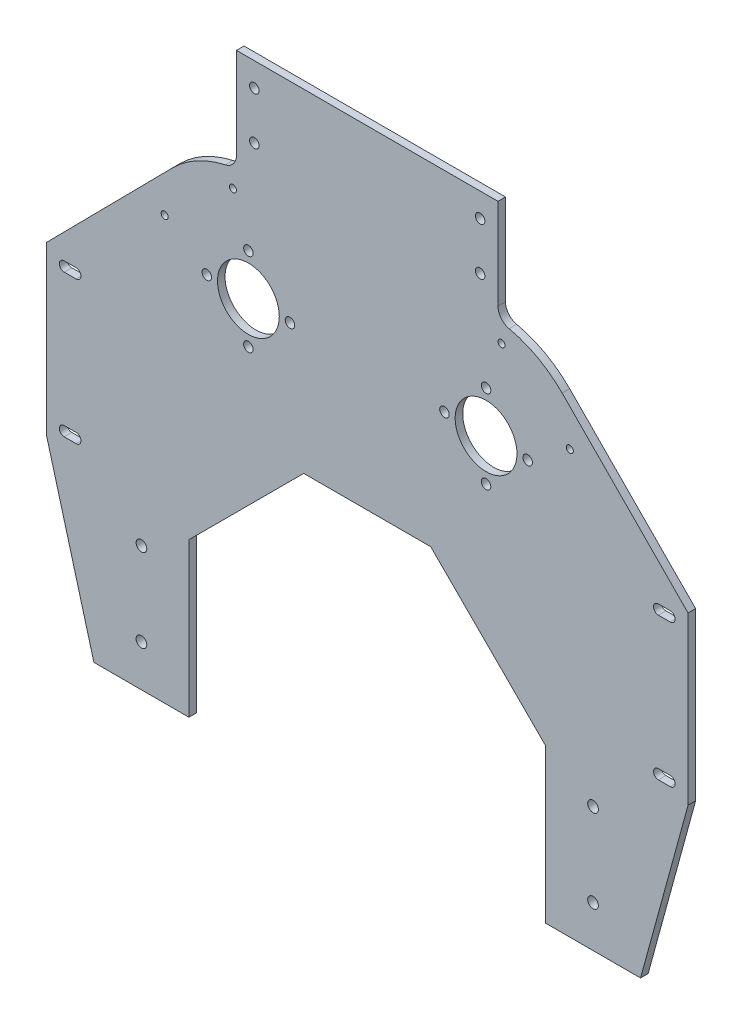
SolidWorks part; units mm, degrees
ref_plane "Front Plane" through (0, 0, 0) normal (0, 0, 1) x (1, 0, 0)
ref_plane "Top Plane" through (0, 0, 0) normal (0, 1, 0) x (1, 0, 0)
ref_plane "Right Plane" through (0, 0, 0) normal (1, 0, 0) x (0, 0, -1)
sketch "Sketch1" plane through (0, 0, 0) normal (0, 0, 1) x (1, 0, 0)
  line L1 (-100, -75) -> (100, -75)
  line L2 (-100, -75) -> (-100, 75)
  line L3 (-100, 75) -> (100, 75)
  line L4 (100, -75) -> (100, 75)
  line L5 (-100, -75) -> (100, 75) construction
  line L6 (-100, 75) -> (100, -75) construction
  line L8 (-47.5, 40) -> (47.5, 40) construction
  line L9 (0, 75) -> (0, -75) construction
  line L10 (-27, -44) -> (27, -44) construction
  line L11 (-27, -44) -> (-27, 28) construction
  line L12 (-27, 28) -> (27, 28) construction
  line L13 (27, -44) -> (27, 28) construction
  line L14 (-27, -44) -> (27, 28) construction
  line L15 (-27, 28) -> (27, -44) construction
  line L23 (-55, 70) -> (55, 70)
  line L24 (-55, 70) -> (-55, -70)
  line L25 (-55, -70) -> (55, -70)
  line L26 (55, 70) -> (55, -70)
  line L27 (-55, 70) -> (55, -70) construction
  line L28 (-55, -70) -> (55, 70) construction
  line L29 (-32.5, 70) -> (32.5, 70) construction
  line L30 (-32.5, 70) -> (-32.5, 55) construction
  line L31 (-32.5, 55) -> (32.5, 55) construction
  line L32 (32.5, 70) -> (32.5, 55) construction
  line L33 (-32.5, 70) -> (32.5, 55) construction
  line L34 (-32.5, 55) -> (32.5, 70) construction
  circle A2 centre (-47.5, 40) radius 2
  circle A3 centre (47.5, 40) radius 2
  circle A4 centre (-27, 28) radius 2 construction
  circle A5 centre (27, 28) radius 2 construction
  circle A6 centre (27, -44) radius 2 construction
  circle A7 centre (-27, -44) radius 2 construction
  circle A8 centre (-47.5, 60) radius 2
  circle A10 centre (47.5, 60) radius 2
  point P0 (0, 0)
  point P15 (0, 40)
  point P18 (0, -8)
  point P56 (0, 0)
  point P63 (0, 62.5)
  dimension "D3" = 4
  dimension "D4" = 20
  dimension "D5" = 4
  dimension "D8" = 4
  dimension "D1" = 150
  dimension "D2" = 200
  dimension "D6" = 72
  dimension "D7" = 54
  dimension "D14" = 30
  dimension "D15" = 140
  dimension "D16" = 110
  dimension "D17" = 95
  dimension "D18" = 12
  dimension "D19" = 15
  dimension "D20" = 65
extrude "Boss-Extrude1" add sketch "Sketch1" along normal blind 3.175 contours L23 L32 L31 L30 L24 L25 L26 A7 A6 A5 A4 A3 A2 | L2 L1 L4 L3
sketch "Sketch2" plane through (0, 0, 0) normal (0, 0, 1) x (1, 0, 0)
  line L0 (-55, -70) -> (-100.8579, -115.8579) construction
  line L1 (-55, 70) -> (-55, -70) construction
  line L2 (-55, -41.7157) -> (-115, -101.7157)
  line L3 (-26.7157, -70) -> (-86.7157, -130)
  line L4 (-55, -70) -> (55, -70) construction
  line L5 (-115, -101.7157) -> (-86.7157, -130)
  line L6 (-115, -101.7157) -> (-115, -183)
  line L7 (-75, -118.2843) -> (-75, -183)
  line L8 (-75, -183) -> (-115, -183)
  line L9 (0, 75) -> (0, -75) construction
  line L10 (-55, -41.7157) -> (-26.7157, -70)
  line L11 (-55, 70) -> (-55, -70) construction
  line L12 (-115, -183) -> (-66.3325, -183) construction
  circle A0 centre (-95, -130.5) radius 2.25
  circle A1 centre (-95, -165.5) radius 2.25
  circle A2 centre (-95, -130.5) radius 2.25 construction
  circle A4 centre (-95, -165.5) radius 2.25 construction
  dimension "D1" = 135
  dimension "D2" = 40
  dimension "D3" = 40
  dimension "D4" = 75
  dimension "D5" = 0
extrude "Boss-Extrude2" add sketch "Sketch2" along normal blind 3.175
mirror "Mirror1" about plane through (0, 0, 0) normal (1, 0, 0) of "Boss-Extrude2"
sketch "Sketch3" plane through (0, 0, 3.175) normal (0, 0, 1) x (1, 0, 0)
  line L0 (0, 31.3301) -> (0, 52.1198) construction
  line L1 (-50, -18) -> (-56.5118, 18.9303) construction
  line L2 (-50, -18) -> (50, -18) construction
  line L3 (-50, -18) -> (-87.5, -18) construction
  line L4 (-50, -18) -> (-85.2385, -5.1742) construction
  circle A0 centre (-50, -18) radius 45
  circle A1 centre (-50, -0.5) radius 2
  circle A2 centre (50, -18) radius 45
  circle A3 centre (-50, -18) radius 30
  circle A4 centre (50, -18) radius 30
  circle A5 centre (-47.5, 40) radius 2 construction
  circle A6 centre (-47.5, 40) radius 2
  circle A7 centre (47.5, 40) radius 2
  circle A8 centre (-32.5, -18) radius 2
  circle A9 centre (-50, -35.5) radius 2
  circle A10 centre (-67.5, -18) radius 2
  circle A11 centre (67.5, -18) radius 2
  circle A12 centre (50, -35.5) radius 2
  circle A13 centre (32.5, -18) radius 2
  circle A14 centre (50, -0.5) radius 2
  circle A15 centre (-50, -18) radius 13
  circle A16 centre (50, -18) radius 13
  circle A17 centre (-56.5118, 18.9303) radius 1.4732
  circle A18 centre (-85.2385, -5.1742) radius 1.4732
  circle A19 centre (-50, -18) radius 37.5 construction
  circle A20 centre (56.5118, 18.9303) radius 1.4732
  circle A21 centre (85.2385, -5.1742) radius 1.4732
  point P28 (-50, -18)
  point P46 (-73.2681, -18.8689)
  line M3 (115, -101.7157) -> (55, -41.7157)
  line M4 (55, -41.7157) -> (55, 70)
  line M6 (-55, 70) -> (-55, -41.7157)
  line M7 (-55, -41.7157) -> (-115, -101.7157)
  line M11 (-75, -118.2843) -> (-26.7157, -70)
  line M12 (-26.7157, -70) -> (26.7157, -70)
  line M13 (26.7157, -70) -> (75, -118.2843)
  circle M17 centre (-47.5, 40) radius 2
  circle M18 centre (47.5, 40) radius 2
  dimension "D1" = 100
  dimension "D2" = 90
  dimension "D3" = 58
  dimension "D4" = 60
  dimension "D5" = 4
  dimension "D7" = 35
  dimension "D8" = 26
  dimension "D9" = 7.5
  dimension "D10" = 2.9464
  dimension "D6" = 4
  dimension "D11" = 80
  dimension "D12" = 20
extrude "Boss-Extrude3" add sketch "Sketch3" against normal up to surface (3.175 mm away) contours A3 M6 M7 | A3 A0 M6 M7 | A3 A0 M7 M11 M12 M6 M17 | A3 M7 M6 | A4 M3 M4 | A4 M4 M3 | A4 A2 M4 M3 | A4 A2 M3 M4 M12 M13 M18
sketch "Sketch4" plane through (0, 0, 3.175) normal (0, 0, 1) x (1, 0, 0)
  line L0 (-135, -75) -> (-60, -75) construction
  line L1 (-60, -40) -> (-113.0534, -40)
  line L2 (-60, -40) -> (-60, -110)
  line L3 (-60, -110) -> (-115, -110) construction
  line L4 (-135, -40) -> (-135, -110)
  line L5 (-60, -40) -> (-135, -110) construction
  line L6 (-60, -110) -> (-135, -40) construction
  line L7 (-135, -110) -> (-115, -183)
  line L9 (-115, -101.7157) -> (-115, -183) construction
  line L10 (-115, -110) -> (-115, -183)
  line L11 (-135, -40) -> (-82.0098, 13.6287)
  line L12 (-113.0534, -40) -> (-135, -40)
  line L13 (-60, -110) -> (-115, -110) construction
  line L14 (-60, -110) -> (-60, -101.7157)
  line L15 (-60, -101.7157) -> (-115, -101.7157)
  line L16 (-115, -110) -> (-115, -101.7157)
  line L17 (-60, -110) -> (-115, -101.7157) construction
  line L18 (-60, -101.7157) -> (-115, -110) construction
  line L19 (-111.1989, -110) -> (-135, -110) construction
  line L21 (-125, -75) -> (-125, -40) construction
  line L22 (-122.5, -45) -> (-127.5, -45) construction
  line L23 (-122.5, -47.05) -> (-127.5, -47.05)
  line L24 (-122.5, -42.95) -> (-127.5, -42.95)
  line L25 (-122.5, -105) -> (-127.5, -105) construction
  line L26 (-122.5, -102.95) -> (-127.5, -102.95)
  line L27 (-122.5, -107.05) -> (-127.5, -107.05)
  arc A0 (-55, 26.7214) -> (-71.0548, -57.7705) centre (-50, -18) ccw construction
  arc A1 (-82.0098, 13.6287) -> (-89.2556, -40) centre (-50, -18) ccw
  circle A2 centre (-125, -45) radius 2.05 construction
  arc A3 (-122.5, -47.05) -> (-122.5, -42.95) centre (-122.5, -45) ccw
  arc A4 (-127.5, -42.95) -> (-127.5, -47.05) centre (-127.5, -45) ccw
  arc A5 (-122.5, -102.95) -> (-122.5, -107.05) centre (-122.5, -105) cw
  arc A6 (-127.5, -107.05) -> (-127.5, -102.95) centre (-127.5, -105) cw
  point P4 (-97.5, -75)
  point P23 (-87.5, -105.8579)
  point P32 (-125, -45)
  point P40 (-125, -105)
  dimension "D7" = 4.1
  dimension "D8" = 2.05
  dimension "D1" = 40
  dimension "D2" = 60
  dimension "D3" = 70
  dimension "D4" = 75
  dimension "D6" = 10
  dimension "D9" = 5
  dimension "D10" = 5
extrude "Boss-Extrude5" add sketch "Sketch4" against normal up to surface (3.175 mm away)
mirror "Mirror2" about plane through (0, 0, 0) normal (1, 0, 0) of "Boss-Extrude5"
fillet "Fillet1" radius 6 2 edges at (55, 26.7214, 1.5875) (-55, 26.7214, 1.5875)
ref_plane "Plane1" through (-55, -6, 3.175) normal (0, -1, 0) x (-1, 0, 0)
sketch "Sketch6" plane through (0, 0, 3.175) normal (0, 0, 1) x (1, 0, 0)
  circle A0 centre (32.5, -18) radius 2 construction
  circle A1 centre (50, -0.5) radius 2 construction
  circle A2 centre (67.5, -18) radius 2 construction
  circle A3 centre (50, -18) radius 13 construction
  circle A4 centre (50, -35.5) radius 2 construction
  circle A5 centre (-50, -18) radius 13 construction
  circle A6 centre (-67.5, -18) radius 2 construction
  circle A7 centre (-50, -35.5) radius 2 construction
  circle A8 centre (-32.5, -18) radius 2 construction
  circle A9 centre (-50, -0.5) radius 2 construction
  circle A10 centre (32.5, -18) radius 2
  circle A11 centre (50, -0.5) radius 2
  circle A12 centre (67.5, -18) radius 2
  circle A13 centre (50, -18) radius 13
  circle A14 centre (50, -35.5) radius 2
  circle A15 centre (-50, -18) radius 13
  circle A16 centre (-67.5, -18) radius 2
  circle A17 centre (-50, -35.5) radius 2
  circle A18 centre (-32.5, -18) radius 2
  circle A19 centre (-50, -0.5) radius 2
extrude "Cut-Extrude1" cut sketch "Sketch6" against normal blind 10
